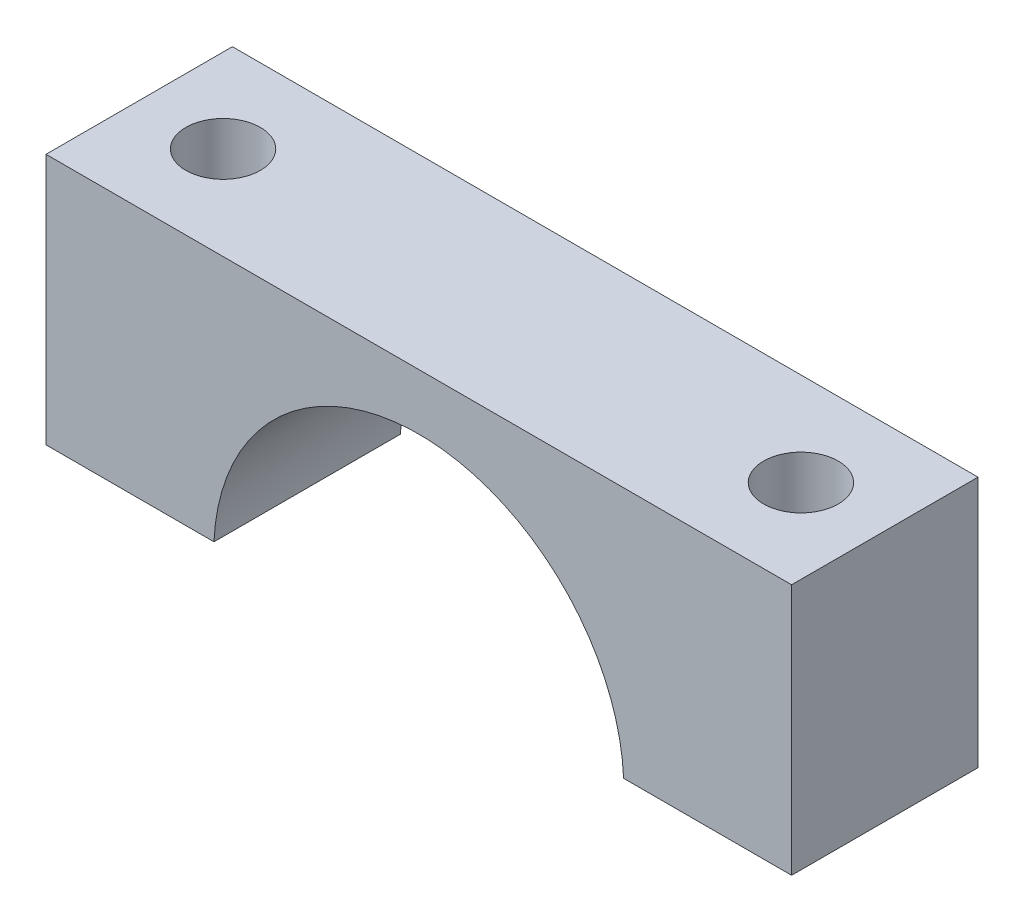
SolidWorks part; units mm, degrees
ref_plane "Plan de face" through (0, 0, 0) normal (0, 0, 1) x (1, 0, 0)
ref_plane "Plan de dessus" through (0, 0, 0) normal (0, 1, 0) x (1, 0, 0)
ref_plane "Plan de droite" through (0, 0, 0) normal (1, 0, 0) x (0, 0, -1)
sketch "Esquisse2" plane through (0, 0, 0) normal (0, 1, 0) x (1, 0, 0)
  line L1 (-15.411, 14.6575) -> (24.589, 14.6575)
  line L2 (-15.411, 14.6575) -> (-15.411, 4.6575)
  line L3 (-15.411, 4.6575) -> (24.589, 4.6575)
  line L4 (24.589, 14.6575) -> (24.589, 4.6575)
  dimension "D1" = 10
  dimension "D2" = 40
extrude "Boss.-Extru.2" add sketch "Esquisse2" along normal blind 13.5
sketch "Esquisse4" plane through (0, 0, -4.6575) normal (0, 0, 1) x (1, 0, 0)
  line L0 (-15.411, 0) -> (24.589, 0) construction
  line L3 (-6.3996, 0) -> (15.5777, 0)
  line L5 (-15.411, 13.5) -> (-15.411, 0) construction
  line L6 (24.589, 13.5) -> (24.589, 0) construction
  line L9 (24.589, 6.75) -> (24.589, 13.5)
  line L10 (24.589, 13.5) -> (-15.411, 13.5)
  line L11 (-15.411, 13.5) -> (-15.411, 6.75)
  arc A0 (15.5777, 0) -> (-6.3996, 0) centre (4.589, -0.5) ccw
  point P6 (4.589, 0)
  dimension "D1" = 11
  dimension "D2" = 14
extrude "Enlèv. mat.-Extru.3" cut sketch "Esquisse4" against normal through all contours L3 A0
sketch "Esquisse5" plane through (0, 13.5, 0) normal (0, 1, 0) x (1, 0, 0)
  line L0 (-15.411, 14.6575) -> (-15.411, 4.6575) construction
  line L1 (4.589, 14.6575) -> (4.589, 4.6575) construction
  line L2 (24.589, 14.6575) -> (-15.411, 14.6575) construction
  line L3 (-15.411, 4.6575) -> (24.589, 4.6575) construction
  circle A0 centre (-10.911, 9.6575) radius 2
  circle A1 centre (20.089, 9.6575) radius 2
  dimension "D1" = 4
  dimension "D2" = 4.5
  dimension "D3" = 5
extrude "Enlèv. mat.-Extru.4" cut sketch "Esquisse5" against normal through all
